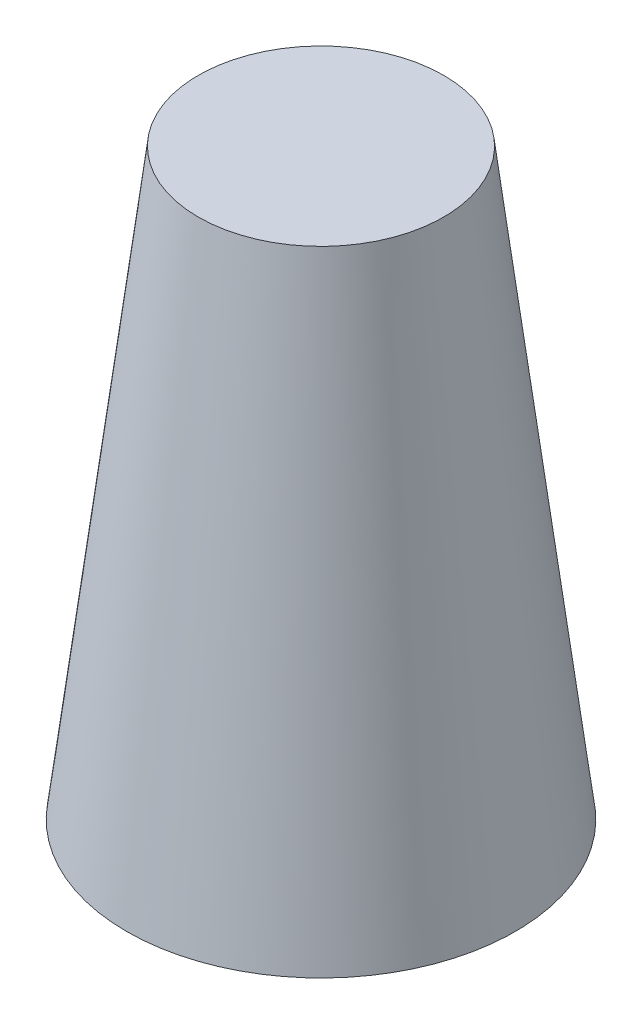
SolidWorks part; units mm, degrees
material "Glass"
ref_plane "Front Plane" through (0, 0, 0) normal (0, 0, 1) x (1, 0, 0)
ref_plane "Top Plane" through (0, 0, 0) normal (0, 1, 0) x (1, 0, 0)
ref_plane "Right Plane" through (0, 0, 0) normal (1, 0, 0) x (0, 0, -1)
sketch "Sketch1" plane through (0, 0, 0) normal (0, 1, 0) x (1, 0, 0)
  circle A0 centre (0, 0) radius 0.635
  dimension "D1" = 1.27
extrude "Boss-Extrude1" add sketch "Sketch1" along normal blind 1.905 draft 7
